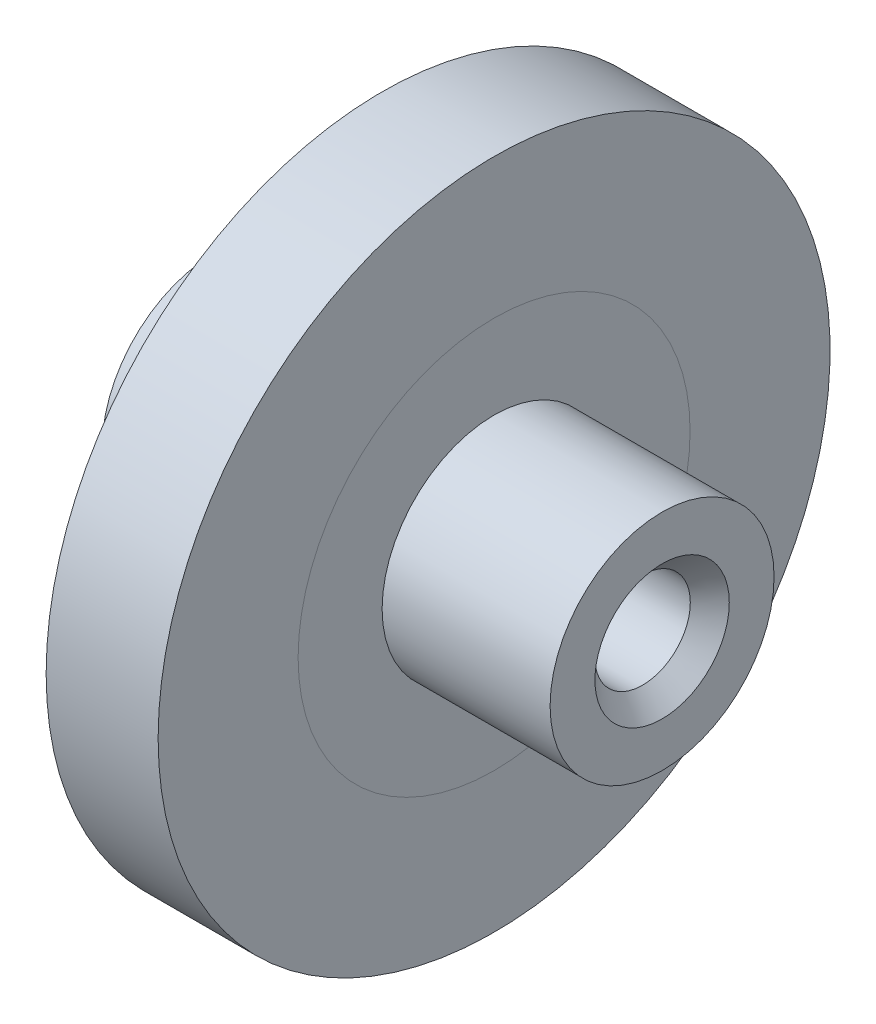
SolidWorks part; units mm, degrees
material "6061-T6 (SS)"
ref_plane "Front Plane" through (0, 0, 0) normal (0, 0, 1) x (1, 0, 0)
ref_plane "Top Plane" through (0, 0, 0) normal (0, 1, 0) x (1, 0, 0)
ref_plane "Right Plane" through (0, 0, 0) normal (1, 0, 0) x (0, 0, -1)
sketch "Sketch1" plane through (0, 0, 0) normal (0, 0, 1) x (1, 0, 0)
  line L0 (0, 0) -> (8669.5734, 0) construction
  line L1 (0, 0) -> (0, 22.0852) construction
  line L7 (0, 19.05) -> (3.175, 19.05)
  line L8 (0, 19.05) -> (0, 0)
  line L9 (0, 0) -> (3.175, 0)
  line L10 (3.175, 19.05) -> (3.175, 0)
  line L11 (3.175, 6.35) -> (12.7, 6.35)
  line L12 (3.175, 6.35) -> (3.175, 0)
  line L13 (3.175, 0) -> (12.7, 0)
  line L14 (12.7, 6.35) -> (12.7, 0)
  dimension "D1" = 6.35
  dimension "D2" = 12.7
  dimension "D3" = 12.7
  dimension "D4" = 38.1
revolve "Revolve1" add sketch "Sketch1" angle 360 about L0
mirror "Mirror1" of "Revolve1"
hole_wizard "1/4-28 Tapped Hole1" positions "Sketch2" profile "Sketch3" tap size "1/4-28" standard "ANSI Inch" end condition through all
sketch "Sketch2" plane through (12.7, 0, 0) normal (1, 0, 0) x (0, 0, -1)
  point P0 (0, 0)
sketch "Sketch3" plane through (12.7, 0, 0) normal (0, 1, 0) x (0, 0, -1)
  line L0 (0, 0) -> (0, 25.4)
  line L1 (0, 25.4) -> (3.3401, 25.4)
  line L2 (2.7051, 24.765) -> (2.7051, 1.1049)
  line L3 (2.7051, 1.1049) -> (3.81, 0)
  line L5 (3.81, 0) -> (0, 0)
  line L6 (-2.7051, 1.1049) -> (-3.81, 0) construction
  line L7 (3.3401, 25.4) -> (2.7051, 24.765)
  line L8 (-3.3401, 25.4) -> (-2.7051, 24.765) construction
  line L11 (0, -6.35) -> (0, 107.95) construction
  dimension "Thru Tap Drill Dia." = 5.4102
  dimension "Thru Tap Drill Depth" = 25.4
  dimension "Near C'Sink Dia." = 7.62
  dimension "Near C'Sink Angle" = 90
  dimension "Far C'Sink Dia." = 6.6802
  dimension "Far C'Sink Angle" = 90
cosmetic thread "Hole Thread1" parameters "D2"=6.35
sketch "Sketch4" plane through (3.175, 0, 0) normal (1, 0, 0) x (0, 0, -1)
  circle A0 centre (0, 0) radius 11.1125
  dimension "D1" = 22.225
split line "Split Line1"
